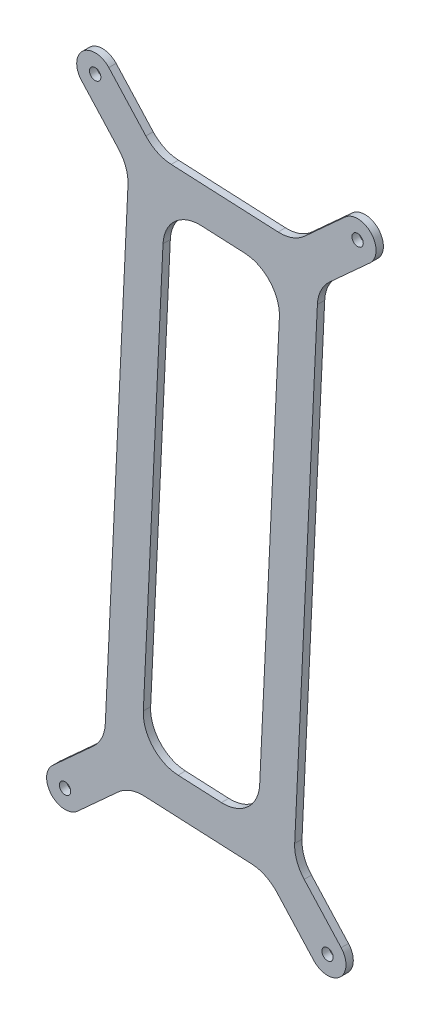
SolidWorks part; units mm, degrees
material "Hexcel AS4C (3000 Filaments)"
ref_plane "Front Plane" through (0, 0, 0) normal (0, 0, 1) x (1, 0, 0)
ref_plane "Top Plane" through (0, 0, 0) normal (0, 1, 0) x (1, 0, 0)
ref_plane "Right Plane" through (0, 0, 0) normal (1, 0, 0) x (0, 0, -1)
sketch "Sketch1" plane through (0, 0, 0) normal (0, 0, 1) x (1, 0, 0)
  line L5 (22.2596, -77.8822) -> (-18.2676, -75.9579)
  line L6 (-29.0036, -64.1515) -> (-22.2596, 77.8822)
  line L18 (29.5388, 75.4227) -> (-22.2596, 77.8822)
  line L19 (22.2596, -77.8822) -> (29.5388, 75.4227)
  line L20 (2.7564, -66.9449) -> (-9.087, -66.3825)
  line L21 (-18.6015, -55.9195) -> (-13.2194, 57.4304)
  line L22 (9.087, 66.3825) -> (-2.7564, 66.9449)
  line L23 (13.2194, -57.4304) -> (18.6015, 55.9195)
  line L24 (-36.6043, -88.6734) -> (-25.4696, -78.5481)
  line L25 (-43.3993, -81.2009) -> (-32.2646, -71.0757)
  line L26 (-29.5388, -75.4227) -> (-22.2596, 77.8822) construction
  line L27 (22.2596, -77.8822) -> (-29.5388, -75.4227) construction
  line L28 (-19.0758, -65.9082) -> (-12.7452, 67.4191) construction
  line L29 (19.0758, 65.9082) -> (-12.7452, 67.4191) construction
  line L30 (12.7452, -67.4191) -> (19.0758, 65.9082) construction
  line L31 (12.7452, -67.4191) -> (-19.0758, -65.9082) construction
  line L33 (28.0379, -91.7427) -> (17.9126, -80.608)
  line L34 (35.5103, -84.9477) -> (25.3851, -73.813)
  line L35 (-35.5103, 84.9477) -> (-25.3851, 73.813)
  line L36 (-28.0379, 91.7427) -> (-17.9126, 80.608)
  line L37 (36.6043, 88.6734) -> (25.4696, 78.5481)
  line L38 (43.3993, 81.2009) -> (32.2646, 71.0757)
  circle A21 centre (-40.0018, -84.9372) radius 1.55
  circle A22 centre (31.7741, -88.3452) radius 1.55
  circle A23 centre (-31.7741, 88.3452) radius 1.55
  circle A24 centre (40.0018, 84.9372) radius 1.55
  circle A25 centre (-40.0018, -84.9372) radius 5.05
  circle A26 centre (31.7741, -88.3452) radius 5.05
  circle A27 centre (40.0018, 84.9372) radius 5.05
  circle A28 centre (-31.7741, 88.3452) radius 5.05
  arc A30 (-32.2646, -71.0757) -> (-29.0036, -64.1515) centre (-38.9924, -63.6772) ccw
  arc A31 (-25.4696, -78.5481) -> (-18.2676, -75.9579) centre (-18.7419, -85.9466) cw
  arc A32 (-13.2194, 57.4304) -> (-2.7564, 66.9449) centre (-3.2307, 56.9561) cw
  arc A33 (9.087, 66.3825) -> (18.6015, 55.9195) centre (8.6127, 56.3938) cw
  arc A34 (2.7564, -66.9449) -> (13.2194, -57.4304) centre (3.2307, -56.9561) ccw
  arc A35 (-9.087, -66.3825) -> (-18.6015, -55.9195) centre (-8.6127, -56.3938) cw
  arc A36 (25.3851, -73.813) -> (22.7948, -66.611) centre (32.7835, -67.0852) cw
  arc A37 (17.9126, -80.608) -> (10.9884, -77.347) centre (10.5141, -87.3357) ccw
  arc A38 (-25.3851, 73.813) -> (-22.7948, 66.611) centre (-32.7835, 67.0852) cw
  arc A39 (-17.9126, 80.608) -> (-10.9884, 77.347) centre (-10.5141, 87.3357) ccw
  arc A40 (25.4696, 78.5481) -> (18.2676, 75.9579) centre (18.7419, 85.9466) cw
  arc A41 (32.2646, 71.0757) -> (29.0036, 64.1515) centre (38.9924, 63.6772) ccw
  point P3 (0, 0)
  point P12 (0, 0)
  point P25 (0, 0)
  dimension "D1" = 10
  dimension "D2" = 3.5
  dimension "D3" = 10
  dimension "D4" = 3.5
  dimension "D5" = 10
extrude "Boss-Extrude1" add sketch "Sketch1" along normal blind 2 contours L24 A31 L5 L19 L18 L6 A30 L25 A25 L20 A35 L21 A32 L22 A33 L23 A34 | A41 L38 A27 L37 A40 L18 L19 | A27 A24 | A37 L33 A26 L34 A36 L19 L5 | A39 L36 A28 L35 A38 L6 L18 | A22 | A21 | A23
